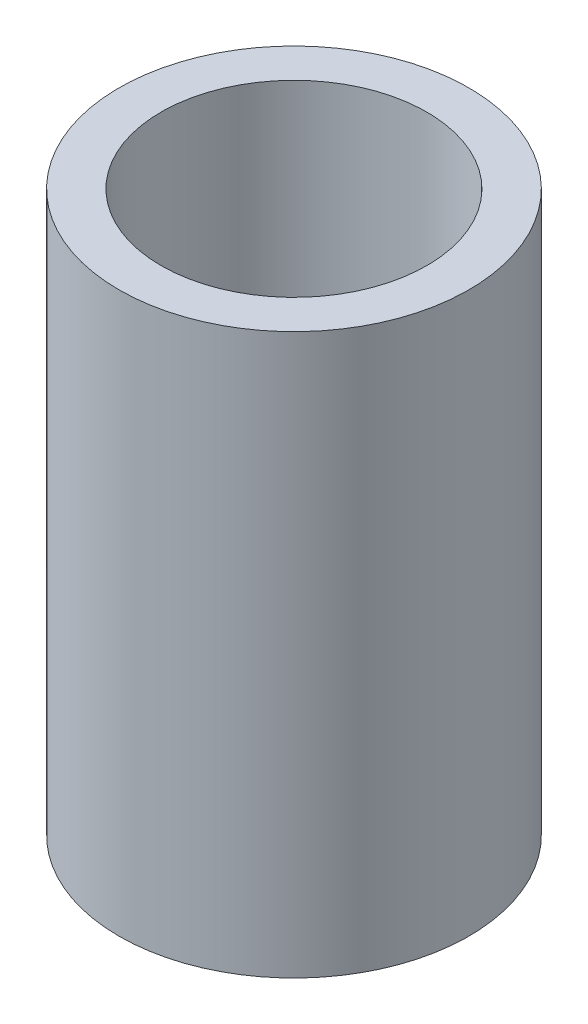
SolidWorks part; units mm, degrees
ref_plane "Front Plane" through (0, 0, 0) normal (0, 0, 1) x (1, 0, 0)
ref_plane "Top Plane" through (0, 0, 0) normal (0, 1, 0) x (1, 0, 0)
ref_plane "Right Plane" through (0, 0, 0) normal (1, 0, 0) x (0, 0, -1)
sketch "Sketch1" plane through (0, 0, 0) normal (0, 1, 0) x (1, 0, 0)
  circle A0 centre (0, 0) radius 9.5
  circle A1 centre (0, 0) radius 12.5
extrude "Boss-Extrude1" add sketch "Sketch1" along normal blind 40
